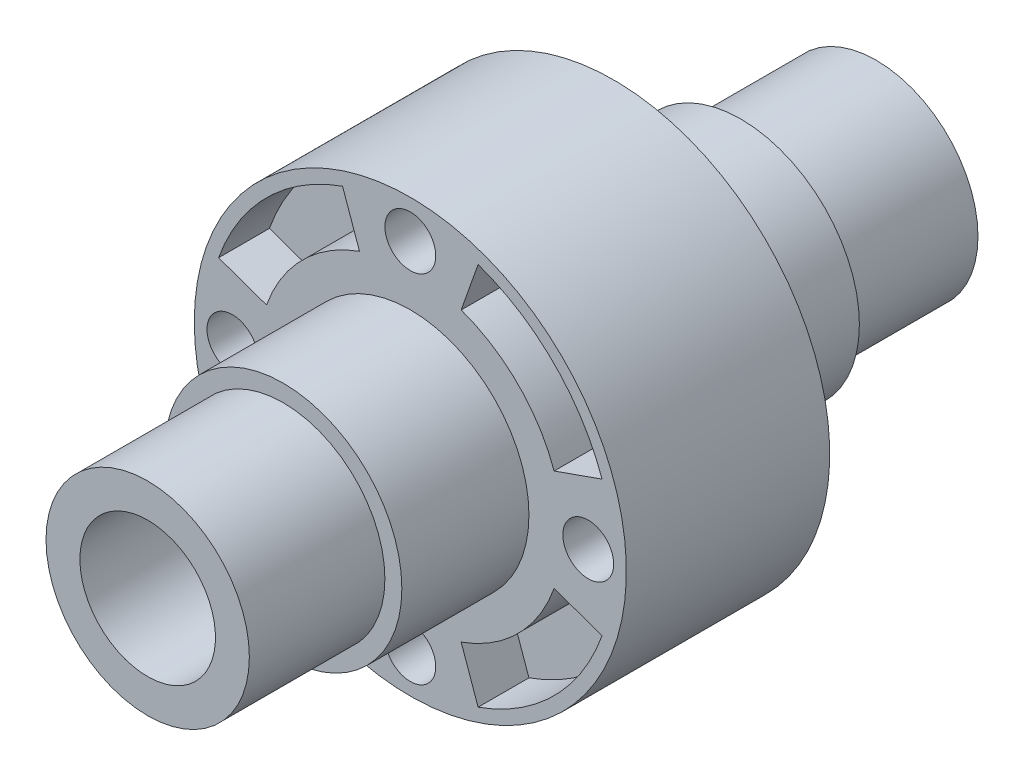
SolidWorks part; units mm, degrees
ref_plane "前视基准面" through (0, 0, 0) normal (0, 0, 1) x (1, 0, 0)
ref_plane "上视基准面" through (0, 0, 0) normal (0, 1, 0) x (1, 0, 0)
ref_plane "右视基准面" through (0, 0, 0) normal (1, 0, 0) x (0, 0, -1)
sketch "草图1" plane through (0, 0, 0) normal (1, 0, 0) x (0, 0, -1)
  line L0 (-21.2214, 0) -> (28.1258, 0) construction
  line L1 (-21.5, 0) -> (-21.5, 6)
  line L2 (-21.5, 6) -> (-13.5, 6)
  line L3 (-13.5, 6) -> (-13.5, 7)
  line L4 (-13.5, 7) -> (-6, 7)
  line L5 (-6, 7) -> (-6, 14)
  line L6 (-6, 14) -> (6, 14)
  line L7 (0, 14) -> (0, 0) construction
  line L8 (6, 7) -> (6, 14)
  line L9 (13.5, 7) -> (6, 7)
  line L10 (13.5, 6) -> (13.5, 7)
  line L11 (21.5, 6) -> (13.5, 6)
  line L12 (21.5, 0) -> (21.5, 6)
  line L13 (-21.5, 0) -> (21.5, 0)
  dimension "D1" = 6
  dimension "D2" = 12
  dimension "D3" = 14
  dimension "D4" = 8
  dimension "D5" = 7.5
  dimension "D6" = 7
revolve "旋转1" add sketch "草图1" angle 360 about L13
sketch "草图2" plane through (0, 0, 6) normal (0, 0, 1) x (1, 0, 0)
  line L0 (0, 0) -> (0, 10.5) construction
  circle A0 centre (0, 0) radius 10.5 construction
  circle A1 centre (0, 10.5) radius 1.5
  circle A2 centre (0, 0) radius 10.5 construction
  circle A3 centre (10.5, 0) radius 1.5
  circle A4 centre (0, 0) radius 10.5 construction
  circle A5 centre (0, -10.5) radius 1.5
  circle A6 centre (0, 0) radius 10.5 construction
  circle A7 centre (-10.5, 0) radius 1.5
  dimension "D1" = 21
  dimension "D2" = 3
  dimension "D3" = 4
extrude "切除-拉伸1" cut sketch "草图2" against normal through all
sketch "草图4" plane through (0, 0, -6) normal (0, 0, -1) x (-1, 0, 0)
  circle A0 centre (0, 0) radius 12.75
  circle A1 centre (0, 0) radius 14 construction
  circle A2 centre (0, 0) radius 14
  dimension "D1" = 25.5
extrude "切除-拉伸4" cut sketch "草图4" against normal through all
sketch "草图5" plane through (0, 0, -6) normal (0, 0, -1) x (-1, 0, 0)
  line L0 (-11.3137, 4) -> (-8.4853, 3)
  line L1 (-4, 11.3137) -> (-3, 8.4853)
  line L2 (4, 11.3137) -> (3, 8.4853)
  line L3 (11.3137, 4) -> (8.4853, 3)
  line L4 (11.3137, -4) -> (8.4853, -3)
  line L5 (4, -11.3137) -> (3, -8.4853)
  line L6 (-4, -11.3137) -> (-3, -8.4853)
  line L7 (-11.3137, -4) -> (-8.4853, -3)
  circle A2 centre (-10.5, 0) radius 1.5 construction
  circle A4 centre (0, 10.5) radius 1.5 construction
  arc A6 (-3, 8.4853) -> (-8.4853, 3) centre (0, 0) ccw
  arc A7 (-4, 11.3137) -> (-11.3137, 4) centre (0, 0) ccw
  arc A8 (8.4853, 3) -> (3, 8.4853) centre (0, 0) ccw
  arc A9 (11.3137, 4) -> (4, 11.3137) centre (0, 0) ccw
  arc A10 (3, -8.4853) -> (8.4853, -3) centre (0, 0) ccw
  arc A11 (4, -11.3137) -> (11.3137, -4) centre (0, 0) ccw
  arc A12 (-8.4853, -3) -> (-3, -8.4853) centre (0, 0) ccw
  arc A13 (-11.3137, -4) -> (-4, -11.3137) centre (0, 0) ccw
  point P25 (0, 0)
  dimension "D3" = 12
  dimension "D4" = 9
  dimension "D1" = 4
  dimension "D2" = 4
  dimension "D5" = 4
extrude "切除-拉伸5" cut sketch "草图5" against normal blind 3
mirror "镜向2" about plane through (0, 0, 0) normal (0, 0, 1) of "切除-拉伸5"
sketch "草图6" plane through (0, 0, -21.5) normal (0, 0, -1) x (-1, 0, 0)
  circle A0 centre (0, 0) radius 4
  dimension "D1" = 8
extrude "切除-拉伸6" cut sketch "草图6" against normal through all
move or copy body "实体-移动/复制1" [suppressed] bodies to move or copy 113
